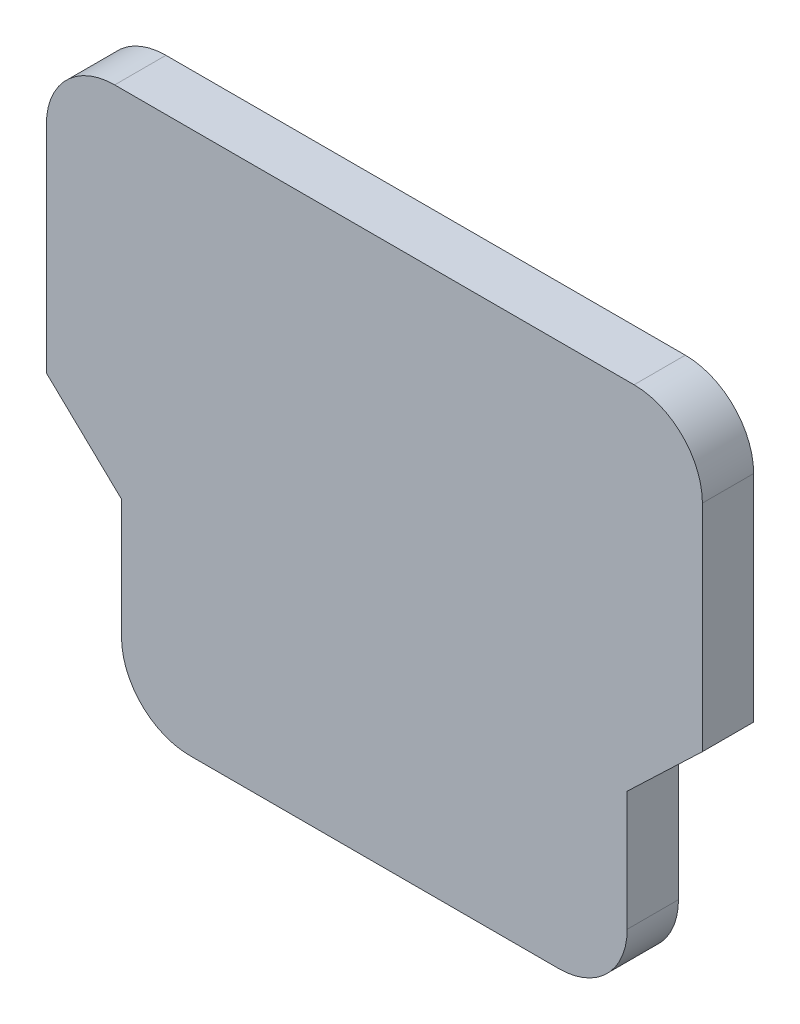
SolidWorks part; units mm, degrees
ref_plane "Płaszczyzna przednia" through (0, 0, 0) normal (0, 0, 1) x (1, 0, 0)
ref_plane "Płaszczyzna górna" through (0, 0, 0) normal (0, 1, 0) x (1, 0, 0)
ref_plane "Płaszczyzna prawa" through (0, 0, 0) normal (1, 0, 0) x (0, 0, -1)
sketch "Szkic1" plane through (0, 0, 0) normal (0, 0, 1) x (1, 0, 0)
  line L0 (-13.2608, -0.4629) -> (14.4711, -0.4629) construction
  line L1 (-10.7054, 7.8371) -> (8.4946, 7.8371)
  line L2 (-10.7054, 7.8371) -> (-10.7054, -0.4629)
  line L3 (-8.5054, -8.0629) -> (6.2946, -8.0629)
  line L4 (8.4946, 7.8371) -> (8.4946, -0.4629)
  line L5 (-10.7054, -2.5629) -> (8.4946, -2.5629) construction
  line L6 (-1.1054, -8.0629) -> (-1.1054, 7.8371) construction
  line L7 (-8.5054, -8.0629) -> (-8.5054, -2.5629)
  line L8 (-8.5054, -2.5629) -> (-10.7054, -0.4629)
  line L9 (6.2946, -8.0629) -> (6.2946, -2.5629)
  line L10 (6.2946, -2.5629) -> (8.4946, -0.4629)
  circle A0 centre (-1.1054, -8.0629) radius 7.4 construction
  dimension "D5" = 14.8
  dimension "D1" = 15.9
  dimension "D2" = 19.2
  dimension "D3" = 8.3
  dimension "D4" = 5.5
extrude "Dodanie-wyciągnięcie1" add sketch "Szkic1" along normal blind 1.5
fillet "Zaokrąglenie1" radius 2 4 edges at (8.4946, 7.8371, 0.75) (-10.7054, 7.8371, 0.75) (6.2946, -8.0629, 0.75) (-8.5054, -8.0629, 0.75)
ref_plane "Płaszczyzna1" through (-1.1054, 0, 0) normal (1, 0, 0) x (0, 0, -1)
